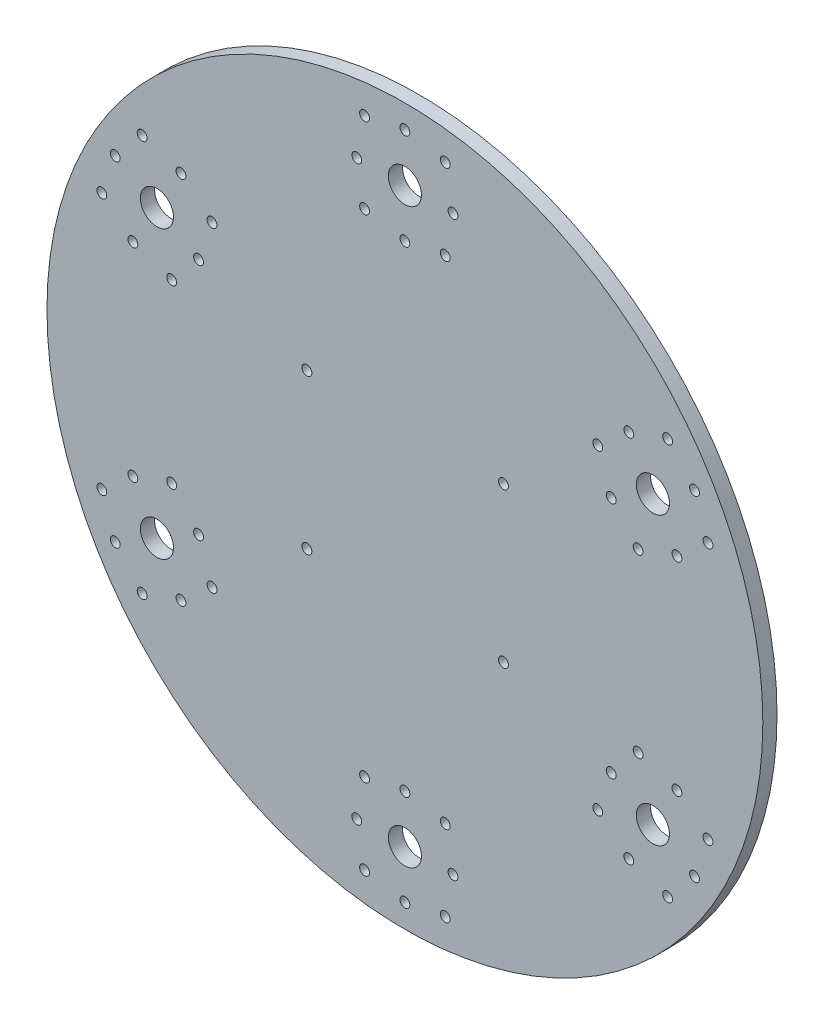
SolidWorks part; units mm, degrees
ref_plane "Front Plane" through (0, 0, 0) normal (0, 0, 1) x (1, 0, 0)
ref_plane "Top Plane" through (0, 0, 0) normal (0, 1, 0) x (1, 0, 0)
ref_plane "Right Plane" through (0, 0, 0) normal (1, 0, 0) x (0, 0, -1)
sketch "Sketch1" plane through (0, 0, 0) normal (0, 0, 1) x (1, 0, 0)
  circle A0 centre (0, 0) radius 80
  circle A1 centre (58.7256, 44.3156) radius 1.1
  circle A2 centre (67.7412, 28.7001) radius 1.1
  circle A3 centre (64.7354, 37.375) radius 1.1
  circle A4 centre (50.0506, 41.3098) radius 1.1
  circle A5 centre (52.1257, 19.6844) radius 1.1
  circle A6 centre (43.1101, 35.2999) radius 1.1
  circle A7 centre (60.8006, 22.6902) radius 1.1
  circle A8 centre (46.1159, 26.625) radius 1.1
  circle A9 centre (55.4256, 32) radius 3.7
  circle A10 centre (-10.75, 64) radius 1.1
  circle A11 centre (-9.0156, 73.0156) radius 1.1
  circle A12 centre (9.0156, 73.0156) radius 1.1
  circle A13 centre (9.0156, 54.9844) radius 1.1
  circle A14 centre (-9.0156, 54.9844) radius 1.1
  circle A15 centre (0, 74.75) radius 1.1
  circle A16 centre (10.75, 64) radius 1.1
  circle A17 centre (0, 53.25) radius 1.1
  circle A18 centre (0, 64) radius 3.7
  circle A19 centre (67.7412, -28.7001) radius 1.1
  circle A20 centre (58.7256, -44.3156) radius 1.1
  circle A21 centre (64.7354, -37.375) radius 1.1
  circle A22 centre (60.8006, -22.6902) radius 1.1
  circle A23 centre (43.1101, -35.2999) radius 1.1
  circle A24 centre (52.1257, -19.6844) radius 1.1
  circle A25 centre (50.0506, -41.3098) radius 1.1
  circle A26 centre (46.1159, -26.625) radius 1.1
  circle A27 centre (55.4256, -32) radius 3.7
  circle A28 centre (9.0156, -73.0156) radius 1.1
  circle A29 centre (-9.0156, -73.0156) radius 1.1
  circle A30 centre (0, -74.75) radius 1.1
  circle A31 centre (10.75, -64) radius 1.1
  circle A32 centre (-9.0156, -54.9844) radius 1.1
  circle A33 centre (9.0156, -54.9844) radius 1.1
  circle A34 centre (-10.75, -64) radius 1.1
  circle A35 centre (0, -53.25) radius 1.1
  circle A36 centre (0, -64) radius 3.7
  circle A37 centre (-58.7256, -44.3156) radius 1.1
  circle A38 centre (-67.7412, -28.7001) radius 1.1
  circle A39 centre (-64.7354, -37.375) radius 1.1
  circle A40 centre (-50.0506, -41.3098) radius 1.1
  circle A41 centre (-52.1257, -19.6844) radius 1.1
  circle A42 centre (-43.1101, -35.2999) radius 1.1
  circle A43 centre (-60.8006, -22.6902) radius 1.1
  circle A44 centre (-46.1159, -26.625) radius 1.1
  circle A45 centre (-55.4256, -32) radius 3.7
  circle A46 centre (-67.7412, 28.7001) radius 1.1
  circle A47 centre (-58.7256, 44.3156) radius 1.1
  circle A48 centre (-64.7354, 37.375) radius 1.1
  circle A49 centre (-60.8006, 22.6902) radius 1.1
  circle A50 centre (-43.1101, 35.2999) radius 1.1
  circle A51 centre (-52.1257, 19.6844) radius 1.1
  circle A52 centre (-50.0506, 41.3098) radius 1.1
  circle A53 centre (-46.1159, 26.625) radius 1.1
  circle A54 centre (-55.4256, 32) radius 3.7
  circle A56 centre (22.0345, 17.272) radius 1.1112
  circle A58 centre (22.0345, -17.272) radius 1.1112
  circle A60 centre (-21.9075, -17.272) radius 1.1112
  circle A62 centre (-21.9075, 17.272) radius 1.1112
  point P17 (55.4256, 32)
  point P22 (55.4256, 32)
  point P36 (0, 64)
  point P41 (0, 64)
  point P44 (0, 64)
  point P45 (0, 64)
  point P47 (55.4256, 32)
  point P48 (55.4256, 32)
  point P61 (55.4256, -32)
  point P66 (55.4256, -32)
  point P69 (55.4256, -32)
  point P70 (55.4256, -32)
  point P83 (0, -64)
  point P88 (0, -64)
  point P91 (0, -64)
  point P92 (0, -64)
  point P105 (-55.4256, -32)
  point P110 (-55.4256, -32)
  point P113 (-55.4256, -32)
  point P114 (-55.4256, -32)
  point P127 (-55.4256, 32)
  point P132 (-55.4256, 32)
  point P135 (-55.4256, 32)
  point P136 (-55.4256, 32)
  point P138 (0, 0)
  dimension "D1" = 160
  dimension "D2" = 10.75
  dimension "D4" = 10.75
  dimension "D5" = 10.75
  dimension "D6" = 64
  dimension "D3" = 7.4
  dimension "D8" = 2.2
  dimension "D11" = 9.0156
  dimension "D14" = 2.2225
  dimension "D19" = 2.2225
  dimension "D20" = 2.2225
  dimension "D21" = 2.2225
  dimension "D7" = 9.0156
  dimension "D10" = 12.75
  dimension "D12" = 45
  dimension "D13" = 6
  dimension "D15" = 43.942
  dimension "D9" = 10.75
  dimension "D16" = 34.544
  dimension "D17" = 21.9075
  dimension "D18" = 17.272
extrude "Boss-Extrude2" add sketch "Sketch1" along normal blind 3.175
